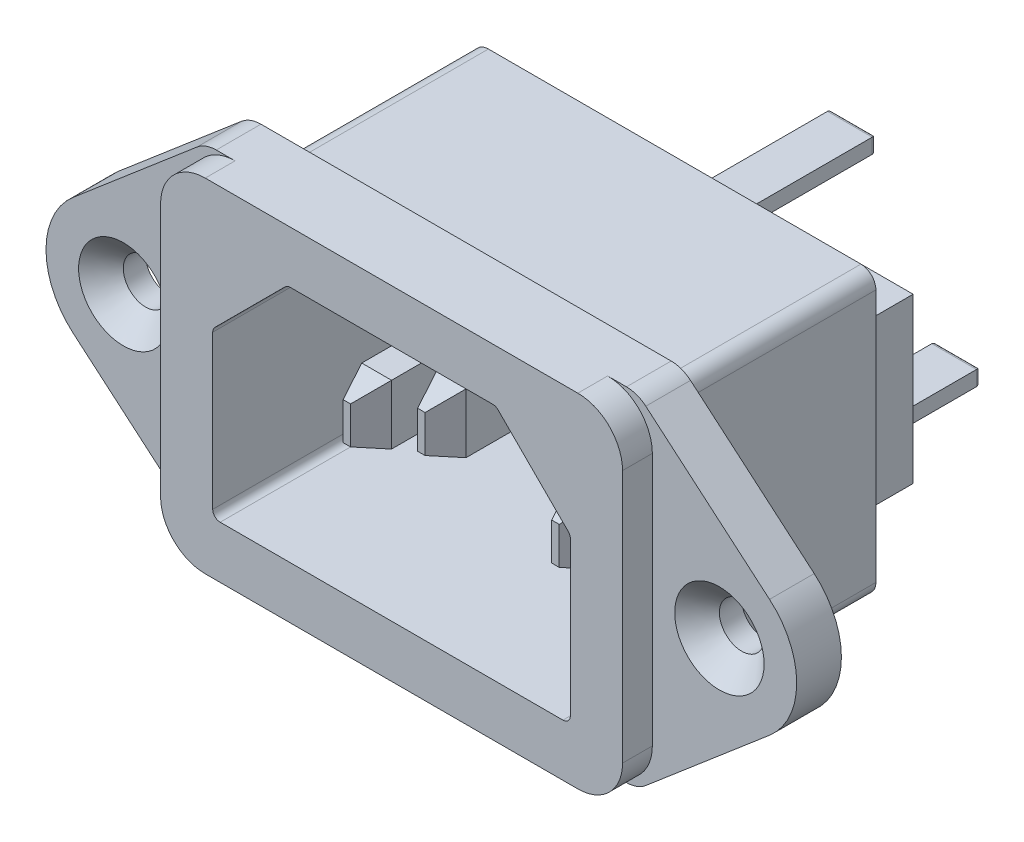
SolidWorks part; units mm, degrees
material "Gummi"
ref_plane "Ebene vorne" through (0, 0, 0) normal (0, 0, 1) x (1, 0, 0)
ref_plane "Ebene oben" through (0, 0, 0) normal (0, 1, 0) x (1, 0, 0)
ref_plane "Ebene rechts" through (0, 0, 0) normal (1, 0, 0) x (0, 0, -1)
sketch "Skizze1" plane through (0, 0, 0) normal (0, 0, 1) x (1, 0, 0)
  line L0 (28, 0) -> (-28, 0) construction
  line L1 (14.5, -11.5) -> (-14.5, -11.5)
  line L2 (14.5, -11.5) -> (14.5, 11.5) construction
  line L3 (14.5, 11.5) -> (-14.5, 11.5)
  line L4 (-14.5, -11.5) -> (-14.5, 11.5) construction
  line L5 (14.5, -11.5) -> (-14.5, 11.5) construction
  line L6 (14.5, 11.5) -> (-14.5, -11.5) construction
  line L7 (-28, 0) -> (-14.5, 11.5) construction
  line L8 (-28, 0) -> (-14.5, -11.5) construction
  line L9 (14.5, -11.5) -> (28, 0) construction
  line L10 (28, 0) -> (14.5, 11.5) construction
  line L11 (20, 0) -> (-20, 0) construction
  line L12 (-20, 0) -> (-23.3641, 3.9491) construction
  line L13 (-20, 0) -> (-23.3641, -3.9491) construction
  line L14 (20, 0) -> (23.3641, 3.9491) construction
  line L15 (20, 0) -> (23.3641, -3.9491) construction
  line L16 (-23.3641, 3.9491) -> (-14.5, 11.5)
  line L17 (-23.3641, -3.9491) -> (-14.5, -11.5)
  line L18 (23.3641, -3.9491) -> (14.5, -11.5)
  line L19 (23.3641, 3.9491) -> (14.5, 11.5)
  circle A0 centre (-20, 0) radius 1.5
  circle A1 centre (20, 0) radius 1.5
  arc A2 (-23.3641, 3.9491) -> (-23.3641, -3.9491) centre (-20, 0) ccw
  arc A3 (23.3641, 3.9491) -> (23.3641, -3.9491) centre (20, 0) cw
  point P0 (0, 0)
  point P9 (0, 0)
  point P12 (0, 0)
  dimension "D5" = 3
  dimension "D1" = 23
  dimension "D2" = 29
  dimension "D3" = 56
  dimension "D4" = 40
extrude "Aufsatz-Linear austragen1" add sketch "Skizze1" along normal blind 3 contours A3 L19 L3 L16 A2 L17 L1 L18 A1 A0
fillet "Verrundung1" radius 2 4 edges at (14.5, -11.5, 1.5) (-14.5, -11.5, 1.5) (14.5, 11.5, 1.5) (-14.5, 11.5, 1.5)
chamfer "Fase1" distance 1.5 angle 45 2 edges at (21.5, 0, 3) (-18.5, 0, 3)
sketch "Skizze2" plane through (0, 0, 3) normal (0, 0, 1) x (1, 0, 0)
  line L0 (13.7636, 11.5) -> (-13.7636, 11.5) construction
  line L1 (-12.5, -11.5) -> (12.5, -11.5)
  line L2 (-15.5, -8.5) -> (-15.5, 8.5)
  line L3 (-12.5, 11.5) -> (12.5, 11.5)
  line L4 (15.5, -8.5) -> (15.5, 8.5)
  line L5 (-15.5, -11.5) -> (15.5, 11.5) construction
  line L6 (-15.5, 11.5) -> (15.5, -11.5) construction
  arc A0 (-12.5, -11.5) -> (-15.5, -8.5) centre (-12.5, -8.5) cw
  arc A1 (12.5, -11.5) -> (15.5, -8.5) centre (12.5, -8.5) ccw
  arc A2 (12.5, 11.5) -> (15.5, 8.5) centre (12.5, 8.5) cw
  arc A3 (-15.5, 8.5) -> (-12.5, 11.5) centre (-12.5, 8.5) cw
  point P0 (0, 0)
  dimension "D2" = 3
  dimension "D1" = 31
extrude "Aufsatz-Linear austragen2" add sketch "Skizze2" along normal blind 2
sketch "Skizze4" plane through (0, 0, 0) normal (0, 0, -1) x (-1, 0, 0)
  line L1 (12.5, -9.5) -> (-12.5, -9.5)
  line L2 (13.5, -8.5) -> (13.5, 8.5)
  line L3 (12.5, 9.5) -> (-12.5, 9.5)
  line L4 (-13.5, -8.5) -> (-13.5, 8.5)
  line L5 (13.5, -9.5) -> (-13.5, 9.5) construction
  line L6 (13.5, 9.5) -> (-13.5, -9.5) construction
  arc A0 (-12.5, -9.5) -> (-13.5, -8.5) centre (-12.5, -8.5) cw
  arc A1 (12.5, -9.5) -> (13.5, -8.5) centre (12.5, -8.5) ccw
  arc A2 (13.5, 8.5) -> (12.5, 9.5) centre (12.5, 8.5) ccw
  arc A3 (-12.5, 9.5) -> (-13.5, 8.5) centre (-12.5, 8.5) ccw
  point P0 (0, 0)
  dimension "D3" = 1
  dimension "D1" = 19
  dimension "D2" = 27
extrude "Aufsatz-Linear austragen3" add sketch "Skizze4" along normal blind 14
sketch "Skizze3" plane through (0, 0, 5) normal (0, 0, 1) x (1, 0, 0)
  line L0 (-12, 3) -> (12, 3) construction
  line L1 (11.5, -8) -> (-11.5, -8)
  line L2 (12, -8) -> (12, 8) construction
  line L3 (12, 8) -> (-12, 8) construction
  line L4 (-12, -8) -> (-12, 8) construction
  line L5 (12, -8) -> (-12, 8) construction
  line L6 (12, 8) -> (-12, -8) construction
  line L7 (7, 8) -> (-7, 8) construction
  line L8 (-12, -7.5) -> (-12, 2.7929)
  line L9 (-11.8536, 3.1464) -> (-7.1464, 7.8536)
  line L10 (7.1464, 7.8536) -> (11.8536, 3.1464)
  line L11 (12, 2.7929) -> (12, -7.5)
  line L12 (6.7929, 8) -> (-6.7929, 8)
  arc A0 (11.5, -8) -> (12, -7.5) centre (11.5, -7.5) ccw
  arc A1 (12, 2.7929) -> (11.8536, 3.1464) centre (11.5, 2.7929) ccw
  arc A2 (6.7929, 8) -> (7.1464, 7.8536) centre (6.7929, 7.5) cw
  arc A3 (-6.7929, 8) -> (-7.1464, 7.8536) centre (-6.7929, 7.5) ccw
  arc A4 (-11.8536, 3.1464) -> (-12, 2.7929) centre (-11.5, 2.7929) ccw
  arc A5 (-11.5, -8) -> (-12, -7.5) centre (-11.5, -7.5) cw
  point P0 (0, 0)
  point P11 (0, 8)
  dimension "D5" = 0.5
  dimension "D1" = 24
  dimension "D2" = 16
  dimension "D3" = 11
  dimension "D4" = 14
extrude "Schnitt-Linear austragen1" cut sketch "Skizze3" against normal blind 17
sketch "Skizze5" plane through (0, 0, -14) normal (0, 0, -1) x (-1, 0, 0)
  line L1 (-12, 5.5) -> (12, 5.5)
  line L2 (-12, 5.5) -> (-12, -5.5)
  line L3 (-12, -5.5) -> (12, -5.5)
  line L4 (12, 5.5) -> (12, -5.5)
  line L5 (-12, 5.5) -> (12, -5.5) construction
  line L6 (-12, -5.5) -> (12, 5.5) construction
  point P0 (0, 0)
  dimension "D1" = 11
  dimension "D2" = 24
extrude "Aufsatz-Linear austragen4" add sketch "Skizze5" along normal blind 4
sketch "Skizze6" plane through (0, 0, -18) normal (0, 0, -1) x (-1, 0, 0)
  line L0 (0, 0) -> (0, 50000) construction
  line L1 (-7, -5) -> (7, -5) construction
  line L2 (12, 5.5) -> (-12, 5.5) construction
  line L3 (1.5, 4.5) -> (-1.5, 4.5)
  line L4 (1.5, 4.5) -> (1.5, 5.5)
  line L5 (1.5, 5.5) -> (-1.5, 5.5)
  line L6 (-1.5, 4.5) -> (-1.5, 5.5)
  line L7 (1.5, 4.5) -> (-1.5, 5.5) construction
  line L8 (1.5, 5.5) -> (-1.5, 4.5) construction
  line L9 (-12, -5.5) -> (12, -5.5) construction
  line L10 (-8.5, -4.5) -> (-5.5, -4.5)
  line L11 (-8.5, -4.5) -> (-8.5, -5.5)
  line L12 (-8.5, -5.5) -> (-5.5, -5.5)
  line L13 (-5.5, -4.5) -> (-5.5, -5.5)
  line L14 (-8.5, -4.5) -> (-5.5, -5.5) construction
  line L15 (-8.5, -5.5) -> (-5.5, -4.5) construction
  line L16 (-12, -5.5) -> (12, -5.5) construction
  line L17 (8.5, -4.5) -> (5.5, -4.5)
  line L18 (8.5, -4.5) -> (8.5, -5.5)
  line L19 (8.5, -5.5) -> (5.5, -5.5)
  line L20 (5.5, -4.5) -> (5.5, -5.5)
  line L21 (8.5, -4.5) -> (5.5, -5.5) construction
  line L22 (8.5, -5.5) -> (5.5, -4.5) construction
  point P3 (0, 5)
  point P6 (0, -5)
  dimension "D1" = 3
  dimension "D2" = 1
  dimension "D3" = 3
  dimension "D4" = 1
  dimension "D5" = 11
extrude "Aufsatz-Linear austragen5" add sketch "Skizze6" along normal blind 8
sketch "Skizze7" plane through (0, 0, -12) normal (0, 0, 1) x (1, 0, 0)
  line L0 (0, 0) -> (0, 50000) construction
  line L3 (-7, -2) -> (7, -2) construction
  line L4 (-11.5, -8) -> (11.5, -8) construction
  line L5 (-6, -4) -> (-8, -4)
  line L6 (-6, -4) -> (-6, 0)
  line L7 (-6, 0) -> (-8, 0)
  line L8 (-8, -4) -> (-8, 0)
  line L9 (-6, -4) -> (-8, 0) construction
  line L10 (-6, 0) -> (-8, -4) construction
  line L11 (6, -4) -> (8, -4)
  line L12 (6, -4) -> (6, 0)
  line L13 (6, 0) -> (8, 0)
  line L14 (8, -4) -> (8, 0)
  line L15 (6, -4) -> (8, 0) construction
  line L16 (6, 0) -> (8, -4) construction
  point P5 (0, -2)
  dimension "D1" = 2
  dimension "D2" = 4
  dimension "D3" = 14
  dimension "D4" = 4
extrude "Aufsatz-Linear austragen6" add sketch "Skizze7" along normal blind 13
sketch "Skizze8" plane through (0, 0, -12) normal (0, 0, 1) x (1, 0, 0)
  line L0 (0, 0) -> (0, 50000) construction
  line L1 (6.7929, 8) -> (-6.7929, 8) construction
  line L2 (-1, 4) -> (1, 4)
  line L3 (-1, 4) -> (-1, 0)
  line L4 (-1, 0) -> (1, 0)
  line L5 (1, 4) -> (1, 0)
  line L6 (-1, 4) -> (1, 0) construction
  line L7 (-1, 0) -> (1, 4) construction
  point P3 (0, 2)
  dimension "D1" = 2
  dimension "D2" = 4
  dimension "D3" = 4
extrude "Aufsatz-Linear austragen7" add sketch "Skizze8" along normal blind 15
chamfer "Fase2" distance 2 distance2 0.75 12 edges at (7, -4, 1) (6, -2, 1) (7, 0, 1) (8, -2, 1) (0, 0, 3) (-1, 2, 3) (0, 4, 3) (1, 2, 3) (-7, 0, 1) (-6, -2, 1) (-7, -4, 1) (-8, -2, 1)
fillet "Verrundung2" radius 0.25 12 edges at (-7, -4.5, -26) (-8.5, -5, -26) (-7, -5.5, -26) (-5.5, -5, -26) (7, -5.5, -26) (8.5, -5, -26) (7, -4.5, -26) (5.5, -5, -26) (0, 5.5, -26) (-1.5, 5, -26) (0, 4.5, -26) (1.5, 5, -26)
